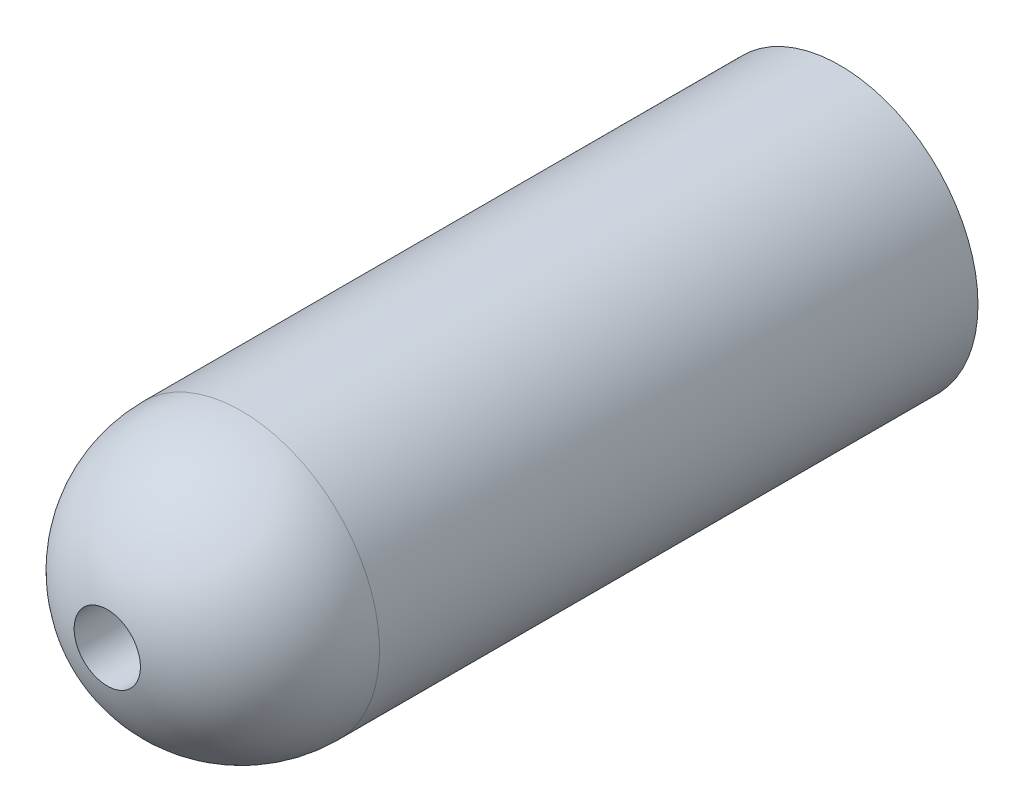
SolidWorks part; units mm, degrees
ref_plane "Front Plane" through (0, 0, 0) normal (0, 0, 1) x (1, 0, 0)
ref_plane "Top Plane" through (0, 0, 0) normal (0, 1, 0) x (1, 0, 0)
ref_plane "Right Plane" through (0, 0, 0) normal (1, 0, 0) x (0, 0, -1)
sketch "Sketch1" plane through (0, 0, 0) normal (0, 0, 1) x (1, 0, 0)
  circle A0 centre (0, 0) radius 4.7625
  dimension "D2" = 9.525
extrude "Boss-Extrude1" add sketch "Sketch1" along normal blind 25.4
fillet "Fillet1" radius 4.7625 1 edges at (4.7625, 0, 25.4)
sketch "Sketch2" plane through (0, 0, 0) normal (0, 0, -1) x (-1, 0, 0)
  circle A0 centre (0, 0) radius 1.143
  dimension "D1" = 2.286
extrude "Cut-Extrude1" cut sketch "Sketch2" against normal blind 25.4
